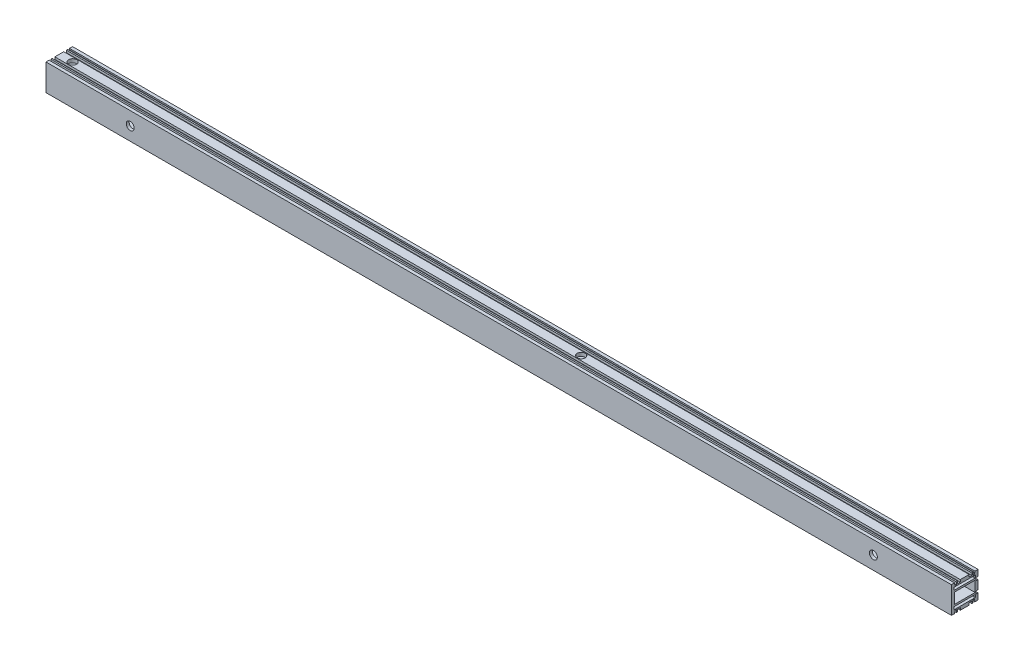
SolidWorks part; units mm, degrees
ref_plane "前视基准面" through (0, 0, 0) normal (0, 0, 1) x (1, 0, 0)
ref_plane "上视基准面" through (0, 0, 0) normal (0, 1, 0) x (1, 0, 0)
ref_plane "右视基准面" through (0, 0, 0) normal (1, 0, 0) x (0, 0, -1)
sketch "草图1" plane through (0, 0, 0) normal (1, 0, 0) x (0, 0, -1)
  line L0 (-15, 15) -> (15, -15) construction
  line L1 (-15, 15) -> (-11.5, 15)
  line L2 (-15, 15) -> (-15, -15)
  line L3 (-15, -15) -> (-11.5, -15)
  line L4 (15, 15) -> (15, 8)
  line L5 (15, 15) -> (-15, -15) construction
  line L6 (-11.5, 15) -> (-11.5, 13.5)
  line L7 (-11.5, 13.5) -> (-11, 13.5)
  line L8 (-11, 13.5) -> (-11, 12)
  line L9 (-11, 12) -> (-9.5, 12)
  line L10 (-9.5, 12) -> (-9.5, 15)
  line L11 (-9.5, 15) -> (-8, 15)
  line L12 (-8, 15) -> (-8, 12.5)
  line L13 (-8, 12.5) -> (-5, 12.5)
  line L14 (-5, 12.5) -> (-5, 15)
  line L15 (-5, 15) -> (5, 15)
  line L16 (0, 21.5201) -> (0, -18.309) construction
  line L17 (0, 55) -> (0, -55) construction
  line L18 (5, 12.5) -> (5, 15)
  line L19 (8, 12.5) -> (5, 12.5)
  line L20 (8, 15) -> (8, 12.5)
  line L21 (9.5, 15) -> (8, 15)
  line L22 (9.5, 12) -> (9.5, 15)
  line L23 (11, 12) -> (9.5, 12)
  line L24 (11, 13.5) -> (11, 12)
  line L25 (11.5, 13.5) -> (11, 13.5)
  line L26 (11.5, 15) -> (11.5, 13.5)
  line L27 (8, 15) -> (9.5, 15)
  line L28 (11.5, 15) -> (15, 15)
  line L29 (-19.8303, 0) -> (22.13, 0) construction
  line L30 (55, 0) -> (-55, 0) construction
  line L31 (8, -15) -> (9.5, -15)
  line L32 (11.5, -15) -> (11.5, -13.5)
  line L33 (11.5, -13.5) -> (11, -13.5)
  line L34 (11, -13.5) -> (11, -12)
  line L35 (11, -12) -> (9.5, -12)
  line L36 (9.5, -12) -> (9.5, -15)
  line L37 (9.5, -15) -> (8, -15)
  line L38 (8, -15) -> (8, -12.5)
  line L39 (8, -12.5) -> (5, -12.5)
  line L40 (5, -12.5) -> (5, -15)
  line L41 (-5, -15) -> (5, -15)
  line L42 (-5, -12.5) -> (-5, -15)
  line L43 (-8, -12.5) -> (-5, -12.5)
  line L44 (-8, -15) -> (-8, -12.5)
  line L45 (-9.5, -15) -> (-8, -15)
  line L46 (-9.5, -12) -> (-9.5, -15)
  line L47 (-11, -12) -> (-9.5, -12)
  line L48 (-11, -13.5) -> (-11, -12)
  line L49 (-11.5, -13.5) -> (-11, -13.5)
  line L50 (-11.5, -15) -> (-11.5, -13.5)
  line L51 (-9.5, -15) -> (-8, -15)
  line L52 (-5, -15) -> (5, -15)
  line L53 (8, -15) -> (9.5, -15)
  line L54 (11.5, -15) -> (15, -15)
  line L55 (15, 8) -> (12.5, 8)
  line L56 (12.5, 8) -> (12.5, 5)
  line L57 (12.5, 5) -> (15, 5)
  line L58 (12.5, -5) -> (15, -5)
  line L59 (12.5, -8) -> (12.5, -5)
  line L60 (15, -8) -> (12.5, -8)
  line L61 (15, 5) -> (15, -5)
  line L62 (15, -8) -> (15, -15)
  line L63 (12, -10.5) -> (12, -8.5)
  line L64 (-11.5, 11) -> (11.5, 11)
  line L65 (-12, 10.5) -> (-12, 8.5)
  line L66 (-11.5, 8) -> (11.5, 8)
  line L67 (12, 10.5) -> (12, 8.5)
  line L68 (-11.5, -8) -> (11.5, -8)
  line L69 (-12, -10.5) -> (-12, -8.5)
  line L70 (-11.5, -11) -> (11.5, -11)
  line L72 (-11.75, 6) -> (11.75, 6)
  line L73 (-11.75, 6) -> (-11.75, -6)
  line L74 (-11.75, -6) -> (11.75, -6)
  line L75 (11.75, 6) -> (11.75, -6)
  arc A0 (12, 8.5) -> (11.5, 8) centre (11.5, 8.5) cw
  arc A1 (11.5, 11) -> (12, 10.5) centre (11.5, 10.5) cw
  arc A2 (-11.5, 11) -> (-12, 10.5) centre (-11.5, 10.5) ccw
  arc A3 (-11.5, 8) -> (-12, 8.5) centre (-11.5, 8.5) cw
  arc A8 (-11.5, -8) -> (-12, -8.5) centre (-11.5, -8.5) ccw
  arc A9 (-11.5, -11) -> (-12, -10.5) centre (-11.5, -10.5) cw
  arc A10 (11.5, -11) -> (12, -10.5) centre (11.5, -10.5) ccw
  arc A11 (12, -8.5) -> (11.5, -8) centre (11.5, -8.5) ccw
  point P69 (12, 11)
  point P72 (-12, 11)
  point P77 (-11, -13.5)
  point P80 (11, -13.5)
  point P83 (11, 13.5)
  point P86 (-11, 13.5)
  point P99 (-12, -11)
  point P100 (12, -11)
  dimension "D17" = 0.5
  dimension "D1" = 3.5
  dimension "D2" = 1.5
  dimension "D3" = 0.5
  dimension "D4" = 1.5
  dimension "D5" = 3
  dimension "D6" = 30
  dimension "D7" = 30
  dimension "D8" = 1.5
  dimension "D9" = 2.5
  dimension "D10" = 3
  dimension "D11" = 2.5
  dimension "D12" = 7
  dimension "D13" = 3
  dimension "D14" = 4
  dimension "D15" = 3
  dimension "D16" = 24
  dimension "D19" = 23.5
  dimension "D20" = 12
extrude "凸台-拉伸1" add sketch "草图1" along normal mid plane 1021
hole_wizard "M6 螺纹孔1" positions "草图3" profile "草图2" tap size "M6" standard "GB"
sketch "草图3" plane through (0, -15, 0) normal (0, -1, 0) x (-1, 0, 0)
  line L0 (-510.5, -15) -> (510.5, -15) construction
  line L1 (510.5, -5) -> (510.5, 5) construction
  point P0 (460.5, 0)
  point P3 (445.5, 0)
  point P6 (-133, 0)
  point P9 (-148, 0)
  point P12 (-218, 0)
  point P15 (-233, 0)
  point P18 (-445.5, 0)
  point P21 (-460.5, 0)
  point P24 (262.5, 0)
  point P26 (211.5, 0)
  dimension "D1" = 15
  dimension "D2" = 15
  dimension "D3" = 51
  dimension "D4" = 248
sketch "草图2" plane through (-460.5, -15, 0) normal (1, 0, 0) x (0, 0, -1)
  line L0 (0, 0) -> (0, 20.5022)
  line L1 (0, 20.5022) -> (2.5, 19)
  line L2 (2.5, 19) -> (2.5, 0)
  line L5 (2.5, 0) -> (0, 0)
  line L10 (0, 20.5022) -> (-2.5, 19) construction
  line L11 (0, -6.35) -> (0, 107.95) construction
  dimension "螺纹孔钻头直径" = 5
  dimension "螺纹孔钻头深度" = 19
  dimension "导头角度" = 118
cosmetic thread "孔螺蚊线1" parameters "D1"=9, "D2"=6
cosmetic thread "孔螺蚊线2" parameters "D1"=9, "D2"=6
cosmetic thread "孔螺蚊线3" parameters "D1"=9, "D2"=6
cosmetic thread "孔螺蚊线4" parameters "D1"=9, "D2"=6
cosmetic thread "孔螺蚊线5" parameters "D1"=9, "D2"=6
cosmetic thread "孔螺蚊线6" parameters "D1"=9, "D2"=6
cosmetic thread "孔螺蚊线7" parameters "D1"=9, "D2"=6
cosmetic thread "孔螺蚊线8" parameters "D1"=9, "D2"=6
cosmetic thread "孔螺蚊线15" parameters "D1"=9, "D2"=6
cosmetic thread "孔螺蚊线16" parameters "D1"=9, "D2"=6
hole_wizard "M6 螺纹孔2" positions "草图5" profile "草图4" tap size "M6" standard "GB"
sketch "草图5" plane through (0, 0, -15) normal (0, 0, -1) x (-1, 0, 0)
  point P0 (460.5, 0)
  point P3 (445.5, 0)
  point P6 (157.5, 0)
  point P9 (142.5, 0)
  point P12 (-445.5, 0)
  point P15 (-460.5, 0)
sketch "草图4" plane through (-460.5, 0, -15) normal (1, 0, 0) x (0, 1, 0)
  line L0 (0, 0) -> (0, 20.5022)
  line L1 (0, 20.5022) -> (2.5, 19)
  line L2 (2.5, 19) -> (2.5, 0)
  line L5 (2.5, 0) -> (0, 0)
  line L10 (0, 20.5022) -> (-2.5, 19) construction
  line L11 (0, -6.35) -> (0, 107.95) construction
  dimension "螺纹孔钻头直径" = 5
  dimension "螺纹孔钻头深度" = 19
  dimension "导头角度" = 118
cosmetic thread "孔螺蚊线9" parameters "D1"=3.25, "D2"=6
cosmetic thread "孔螺蚊线10" parameters "D1"=3.25, "D2"=6
cosmetic thread "孔螺蚊线11" parameters "D1"=3.25, "D2"=6
cosmetic thread "孔螺蚊线12" parameters "D1"=3.25, "D2"=6
cosmetic thread "孔螺蚊线13" parameters "D1"=3.25, "D2"=6
cosmetic thread "孔螺蚊线14" parameters "D1"=3.25, "D2"=6
sketch "草图6" plane through (0, 15, 0) normal (0, 1, 0) x (1, 0, 0)
  line L0 (510.5, 15) -> (-510.5, 15) construction
  line L1 (510.5, 15) -> (-510.5, 15) construction
  line L2 (-510.5, -5) -> (-510.5, 5) construction
  line L3 (510.5, -5) -> (510.5, 5) construction
  circle A0 centre (-495.5, 0) radius 4.5
  circle A1 centre (78, 0) radius 4.5
  dimension "D4" = 9
  dimension "D6" = 9
  dimension "D1" = 15
  dimension "D2" = 15
  dimension "D3" = 15
  dimension "D5" = 432.5
extrude "切除-拉伸1" cut sketch "草图6" against normal through all
sketch "草图7" plane through (0, 0, 15) normal (0, 0, 1) x (1, 0, 0)
  line L0 (510.5, 15) -> (-510.5, 15) construction
  line L1 (-510.5, 15) -> (-510.5, -15) construction
  line L2 (510.5, 15) -> (510.5, -15) construction
  circle A0 centre (-415.5, 0) radius 4.5
  circle A1 centre (422.5, 0) radius 4.5
  dimension "D2" = 9
  dimension "D5" = 9
  dimension "D1" = 15
  dimension "D3" = 95
  dimension "D4" = 15
  dimension "D6" = 88
extrude "切除-拉伸2" cut sketch "草图7" against normal through all
hole_wizard "M4 螺纹孔1" positions "草图9" profile "草图8" tap size "M4" standard "GB"
sketch "草图9" plane through (0, 0, -15) normal (0, 0, -1) x (-1, 0, 0)
  line L0 (-510.5, -15) -> (510.5, -15) construction
  line L1 (510.5, 5) -> (510.5, -5) construction
  point P0 (343.5, 0)
  dimension "D1" = 15
  dimension "D2" = 167
sketch "草图8" plane through (-343.5, 0, -15) normal (1, 0, 0) x (0, 1, 0)
  line L0 (0, 0) -> (0, 12.4914)
  line L1 (0, 12.4914) -> (1.65, 11.5)
  line L2 (1.65, 11.5) -> (1.65, 0)
  line L5 (1.65, 0) -> (0, 0)
  line L10 (0, 12.4914) -> (-1.65, 11.5) construction
  line L11 (0, -6.35) -> (0, 107.95) construction
  dimension "螺纹孔钻头直径" = 3.3
  dimension "螺纹孔钻头深度" = 11.5
  dimension "导头角度" = 118
cosmetic thread "孔螺蚊线17" parameters "D1"=3.25, "D2"=4
